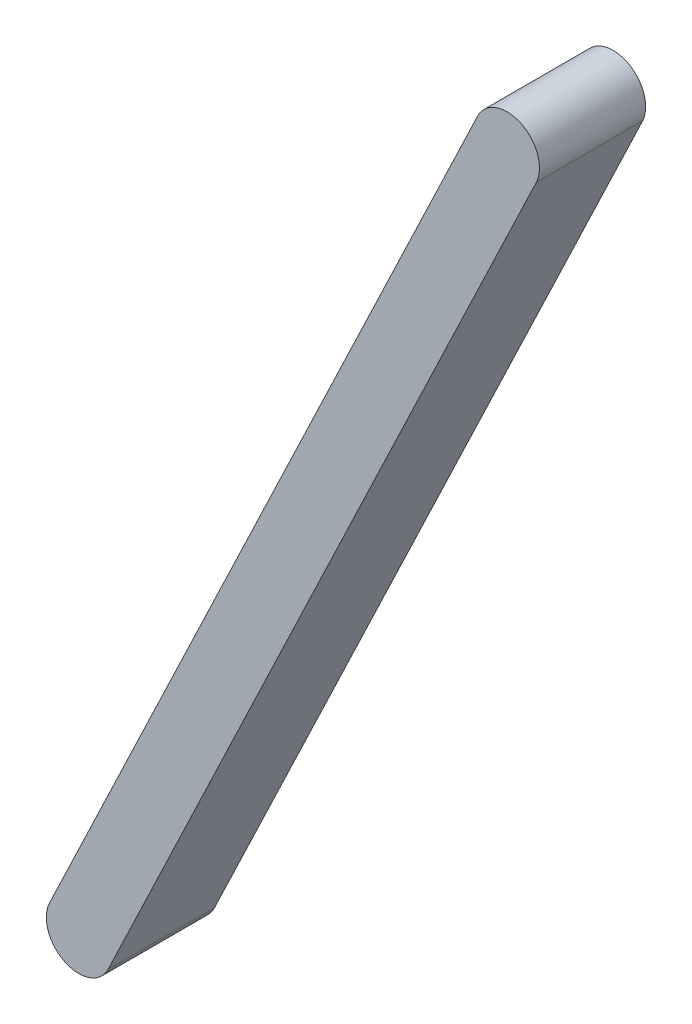
SolidWorks part; units mm, degrees
material "7075-T6 (SN)"
ref_plane "前视基准面" through (0, 0, 0) normal (0, 0, 1) x (1, 0, 0)
ref_plane "上视基准面" through (0, 0, 0) normal (0, 1, 0) x (1, 0, 0)
ref_plane "右视基准面" through (0, 0, 0) normal (1, 0, 0) x (0, 0, -1)
sketch "草图1" plane through (0, 0, 0) normal (0, 0, 1) x (1, 0, 0)
  line L0 (170.8211, -70.014) -> (178.8831, -53.1508) construction
  line L1 (170.2683, -69.7498) -> (178.3304, -52.8865)
  line L2 (171.3738, -70.2783) -> (179.4359, -53.4151)
  arc A0 (170.2683, -69.7498) -> (171.3738, -70.2783) centre (170.8211, -70.014) ccw
  arc A1 (179.4359, -53.4151) -> (178.3304, -52.8865) centre (178.8831, -53.1508) ccw
  point P2 (174.8521, -61.5824)
extrude "凸台-拉伸1" add sketch "草图1" along normal blind 2
